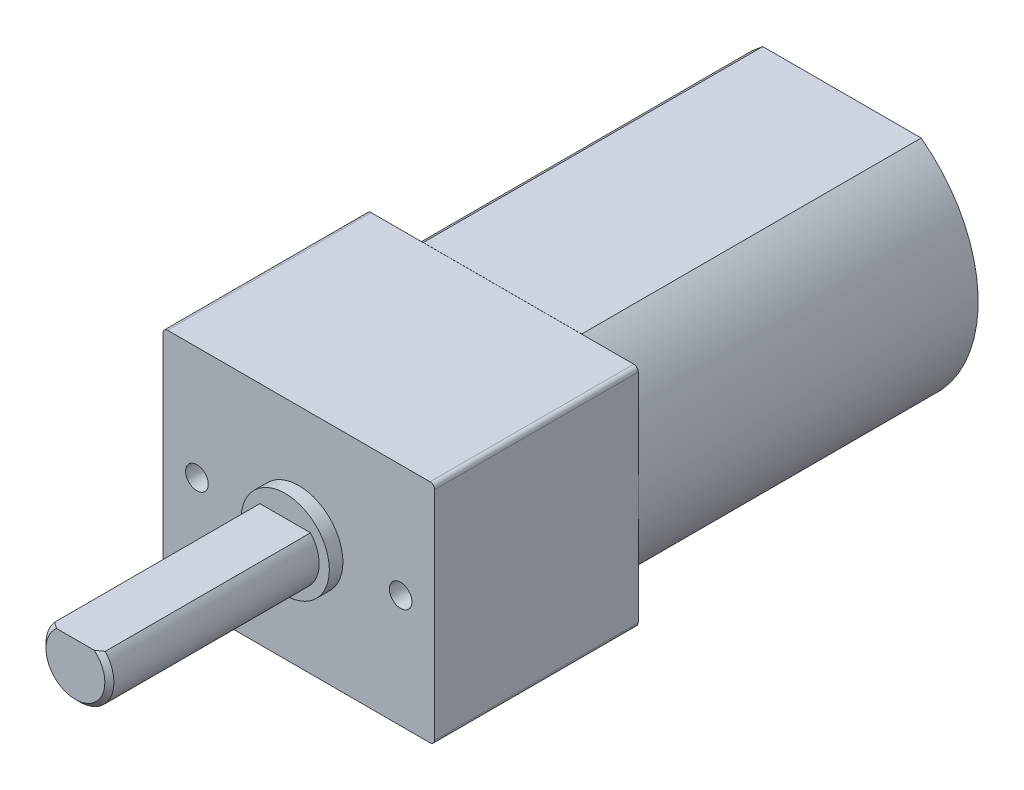
SolidWorks part; units mm, degrees
ref_plane "Alzado" through (0, 0, 0) normal (0, 0, 1) x (1, 0, 0)
ref_plane "Planta" through (0, 0, 0) normal (0, 1, 0) x (1, 0, 0)
ref_plane "Vista lateral" through (0, 0, 0) normal (1, 0, 0) x (0, 0, -1)
sketch "Croquis1" plane through (0, 0, 0) normal (0, 0, 1) x (1, 0, 0)
  line L1 (-3.5, -5) -> (3.5, -5)
  line L3 (-3.5, 5) -> (3.5, 5)
  line L5 (-3.5, -5) -> (3.5, 5) construction
  line L6 (-3.5, 5) -> (3.5, -5) construction
  arc A0 (3.5, 5) -> (3.5, -5) centre (-0.2022, 0) cw
  arc A1 (-3.5, 5) -> (-3.5, -5) centre (0.2984, 0) ccw
  point P0 (0, 0)
  point P8 (6.0193, 0)
  point P9 (-5.9807, 0)
  dimension "D2" = 10
  dimension "D3" = 12
  dimension "D1" = 7
extrude "Saliente-Extruir1" add sketch "Croquis1" along normal blind 15
sketch "Croquis2" plane through (0, 0, 0) normal (0, 0, -1) x (-1, 0, 0)
  circle A0 centre (0, 0) radius 2.5
  dimension "D1" = 5
extrude "Saliente-Extruir2" add sketch "Croquis2" along normal blind 1
sketch "Croquis3" plane through (0, 0, 15) normal (0, 0, 1) x (1, 0, 0)
  line L1 (-6, -4.995) -> (6, -4.995)
  line L2 (-6, -4.995) -> (-6, 4.995)
  line L3 (-6, 4.995) -> (6, 4.995)
  line L4 (6, -4.995) -> (6, 4.995)
  line L5 (-6, -4.995) -> (6, 4.995) construction
  line L6 (-6, 4.995) -> (6, -4.995) construction
  point P0 (0, 0)
  dimension "D1" = 9.99
  dimension "D2" = 12
extrude "Saliente-Extruir3" add sketch "Croquis3" along normal blind 9
fillet "Redondeo1" radius 0.2 4 edges at (6, -4.995, 19.5) (-6, -4.995, 19.5) (-6, 4.995, 19.5) (6, 4.995, 19.5)
sketch "Croquis4" plane through (0, 0, 24) normal (0, 0, 1) x (1, 0, 0)
  circle A0 centre (0, 0) radius 1.95
  dimension "D1" = 3.9
extrude "Saliente-Extruir4" add sketch "Croquis4" along normal blind 0.6
sketch "Croquis5" plane through (0, 0, 24.6) normal (0, 0, 1) x (1, 0, 0)
  line L0 (0, -1.5) -> (0, 1) construction
  line L1 (-1.118, 1) -> (1.118, 1)
  arc A0 (-1.118, 1) -> (1.118, 1) centre (0, 0) ccw
  point P9 (0, 1)
  dimension "D1" = 3
  dimension "D2" = 2.5
extrude "Saliente-Extruir5" add sketch "Croquis5" along normal blind 9.27
chamfer "Chaflán1" distance 0.2 angle 45 1 edges at (0, -1.5, 33.87)
sketch "Croquis6" plane through (0, 0, 24) normal (0, 0, 1) x (1, 0, 0)
  line L0 (0, 4.995) -> (0, -4.995) construction
  line L1 (5.8, 4.995) -> (-5.8, 4.995) construction
  line L2 (-5.8, -4.995) -> (5.8, -4.995) construction
  circle A0 centre (-4.5, 0) radius 0.5
  circle A1 centre (4.5, 0) radius 0.5
  dimension "D1" = 1
  dimension "D2" = 1
  dimension "D3" = 4.5
  dimension "D4" = 4.5
extrude "Cortar-Extruir1" cut sketch "Croquis6" against normal blind 2
